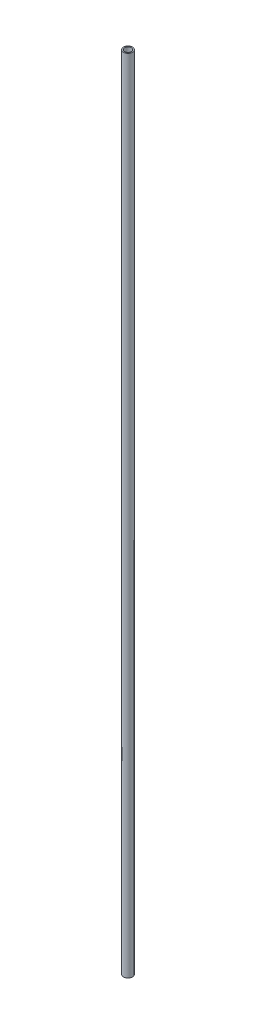
SolidWorks part; units mm, degrees
material "Hexcel AS4C (3000 Filaments)"
ref_plane "Front Plane" through (0, 0, 0) normal (0, 0, 1) x (1, 0, 0)
ref_plane "Top Plane" through (0, 0, 0) normal (0, 1, 0) x (1, 0, 0)
ref_plane "Right Plane" through (0, 0, 0) normal (1, 0, 0) x (0, 0, -1)
sketch "Sketch1" plane through (0, 0, 0) normal (0, 1, 0) x (1, 0, 0)
  circle A0 centre (0, 0) radius 4
  circle A1 centre (0, 0) radius 3
  dimension "D1" = 8
  dimension "D2" = 6
extrude "Boss-Extrude1" add sketch "Sketch1" against normal mid plane 710
